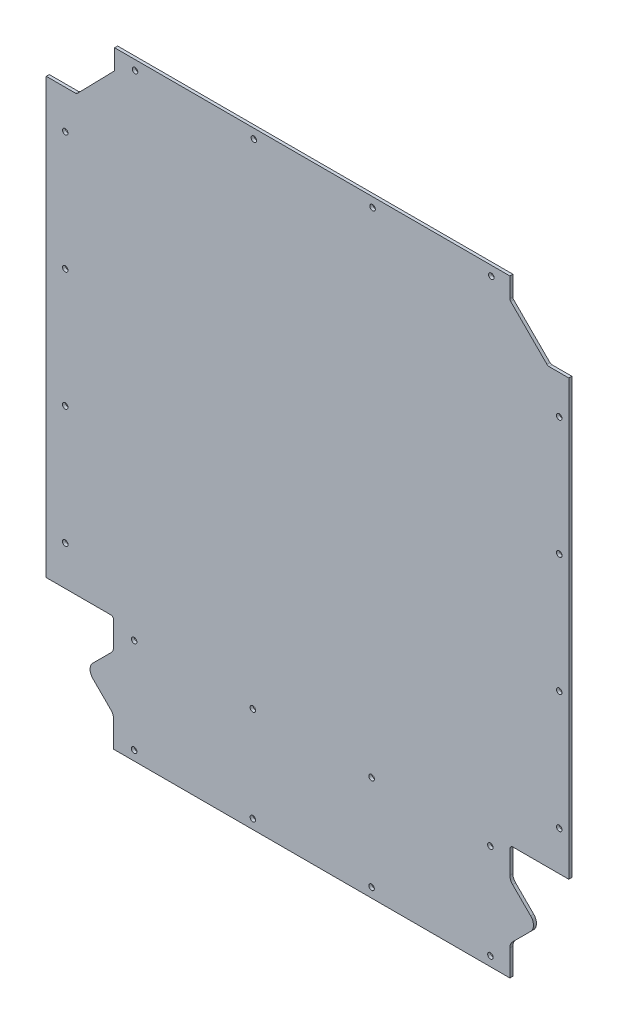
SolidWorks part; units mm, degrees
ref_plane "Front Plane" through (0, 0, 0) normal (0, 0, 1) x (1, 0, 0)
ref_plane "Top Plane" through (0, 0, 0) normal (0, 1, 0) x (1, 0, 0)
ref_plane "Right Plane" through (0, 0, 0) normal (1, 0, 0) x (0, 0, -1)
sketch "Sketch2" plane through (0, 0, 0) normal (0, 0, 1) x (1, 0, 0)
  line L1 (0, 0) -> (550, 0)
  line L2 (0, 0) -> (0, 640)
  line L3 (0, 640) -> (550, 640)
  line L4 (550, 0) -> (550, 640)
  dimension "D1" = 640
  dimension "D2" = 550
extrude "Boss-Extrude1" add sketch "Sketch2" along normal blind 3.175
sketch "Sketch3" plane through (0, 0, 3.175) normal (0, 0, 1) x (1, 0, 0)
  line L0 (0, 640) -> (0, 578)
  line L1 (0, 640) -> (0, 0) construction
  line L2 (32, 578) -> (72, 619)
  line L3 (550, 640) -> (0, 640) construction
  line L4 (72, 640) -> (0, 640)
  line L5 (0, 0) -> (550, 0) construction
  line L6 (275, 0) -> (275, 640) construction
  line L7 (488, 618) -> (488, 640)
  line L8 (528, 578) -> (550, 578)
  line L9 (488, 640) -> (550, 640)
  line L10 (0, 121) -> (71, 121)
  line L11 (71, 121) -> (71, 89.5)
  line L12 (71, 89.5) -> (42, 60.5)
  line L13 (42, 60.5) -> (71, 31.5)
  line L14 (71, 31.5) -> (71, 0)
  line L15 (71, 0) -> (0, 0)
  line L16 (0, 0) -> (0, 121)
  line L17 (550, 0) -> (550, 121)
  line L18 (488, 0) -> (550, 0)
  line L19 (488, 31.5) -> (488, 0)
  line L20 (517, 60.5) -> (488, 31.5)
  line L21 (488, 89.5) -> (517, 60.5)
  line L22 (488, 121) -> (488, 89.5)
  line L23 (550, 121) -> (488, 121)
  line L24 (32, 578) -> (0, 578)
  line L25 (72, 619) -> (72, 640)
  line L26 (528, 578) -> (488, 618)
  line L27 (550, 640) -> (550, 578)
  dimension "D1" = 32
  dimension "D2" = 121
  dimension "D3" = 29
  dimension "D4" = 71
  dimension "D5" = 62
  dimension "D6" = 62
  dimension "D7" = 22
  dimension "D8" = 72
  dimension "D9" = 21
extrude "Cut-Extrude1" cut sketch "Sketch3" against normal through all
fillet "Fillet1" radius 10 6 edges at (517, 60.5, 1.5875) (42, 60.5, 1.5875) (488, 31.5, 1.5875) (488, 89.5, 1.5875) (71, 31.5, 1.5875) (71, 89.5, 1.5875)
fillet "Fillet2" radius 3.175 6 edges at (488, 618, 1.5875) (528, 578, 1.5875) (32, 578, 1.5875) (72, 619, 1.5875) (488, 121, 1.5875) (71, 121, 1.5875)
hole_wizard "M5 Clearance Hole1" positions "3DSketch1" profile "Sketch4" hole size "M5" standard "ANSI Metric" end condition through all
sketch3d "3DSketch1"
  line L0 (488, 640, 3.175) -> (72, 640, 3.175) construction
  line L1 (72, 620.2922, 3.175) -> (72, 640, 3.175) construction
  point P0 (93.5, 630, 3.175)
  dimension "D1" = 10
  dimension "D2" = 21.5
sketch "Sketch4" plane through (93.5, 630, 3.175) normal (1, 0, 0) x (0, -1, 0)
  line L0 (0, 0) -> (0, 3.175)
  line L1 (0, 3.175) -> (2.9, 3.175)
  line L2 (2.9, 3.175) -> (2.9, 0)
  line L5 (2.9, 0) -> (0, 0)
  line L11 (0, -6.35) -> (0, 107.95) construction
  dimension "Thru Hole Dia." = 5.8
  dimension "Thru Hole Depth" = 3.175
pattern_linear "LPattern1" count 4 spacing 125 along (1, 0, 0) of "M5 Clearance Hole1"
hole_wizard "M5 Clearance Hole2" positions "3DSketch2" profile "Sketch5" hole size "M5" standard "ANSI Metric" end condition through all
sketch3d "3DSketch2"
  line L0 (20, 162.5, 3.175) -> (540, 162.5, 3.175) construction
  line L2 (0, 578, 3.175) -> (0, 121, 3.175) construction
  line L3 (20, 162.5, 3.175) -> (0, 162.5, 3.175) construction
  line L5 (540, 162.5, 3.175) -> (550, 162.5, 3.175) construction
  line L6 (550, 121, 3.175) -> (550, 578, 3.175) construction
  line L8 (67.825, 121, 3.175) -> (0, 121, 3.175) construction
  point P0 (20, 162.5, 3.175)
  point P2 (540, 162.5, 3.175)
  dimension "D1" = 41.5
  dimension "D2" = 20
  dimension "D3" = 10
sketch "Sketch5" plane through (20, 162.5, 3.175) normal (1, 0, 0) x (0, -1, 0)
  line L0 (0, 0) -> (0, 3.175)
  line L1 (0, 3.175) -> (2.9, 3.175)
  line L2 (2.9, 3.175) -> (2.9, 0)
  line L5 (2.9, 0) -> (0, 0)
  line L11 (0, -6.35) -> (0, 107.95) construction
  dimension "Thru Hole Dia." = 5.8
  dimension "Thru Hole Depth" = 3.175
pattern_linear "LPattern2" count 4 spacing 125 along (0, 1, 0) of "M5 Clearance Hole2"
hole_wizard "M5 Clearance Hole3" positions "3DSketch3" profile "Sketch6" hole size "M5" standard "ANSI Metric" end condition through all
sketch3d "3DSketch3"
  line L0 (92.5, 110, 3.175) -> (92.5, 10, 3.175) construction
  line L2 (71, 0, 3.175) -> (488, 0, 3.175) construction
  point P0 (92.5, 110, 3.175)
  point P2 (92.5, 10, 3.175)
  dimension "D1" = 10
  dimension "D2" = 100
  dimension "D3" = 21.5
sketch "Sketch6" plane through (92.5, 110, 3.175) normal (1, 0, 0) x (0, -1, 0)
  line L0 (0, 0) -> (0, 3.175)
  line L1 (0, 3.175) -> (2.9, 3.175)
  line L2 (2.9, 3.175) -> (2.9, 0)
  line L5 (2.9, 0) -> (0, 0)
  line L11 (0, -6.35) -> (0, 107.95) construction
  dimension "Thru Hole Dia." = 5.8
  dimension "Thru Hole Depth" = 3.175
pattern_linear "LPattern3" count 4 spacing 125 along (1, 0, 0) of "M5 Clearance Hole3"
